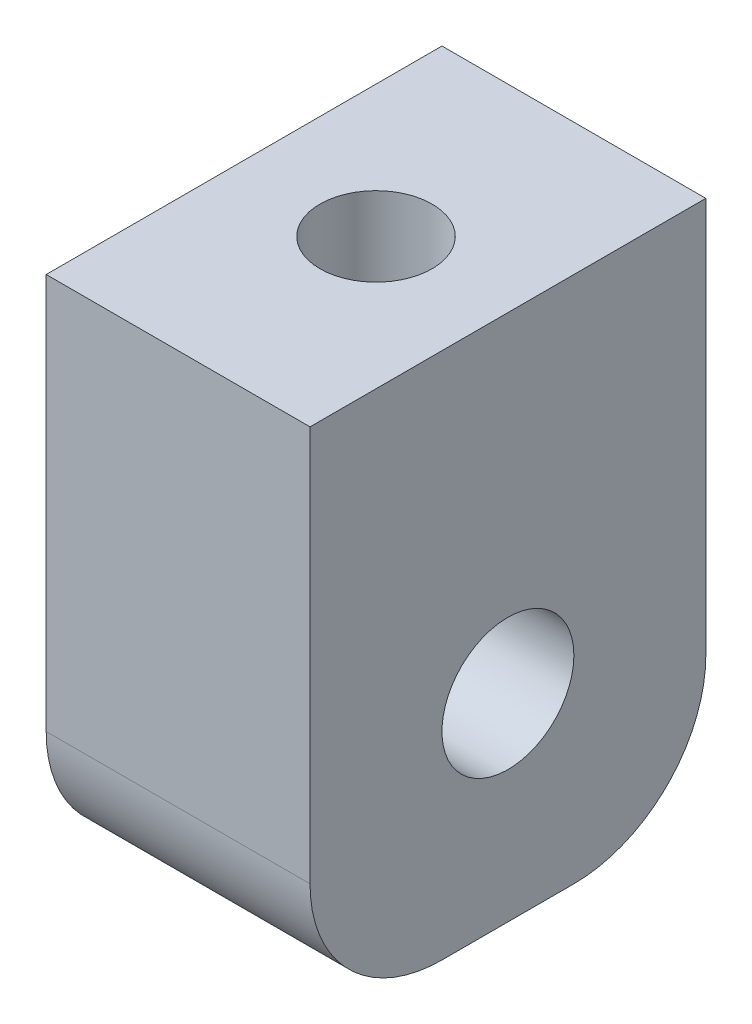
SolidWorks part; units mm, degrees
ref_plane "Front Plane" through (0, 0, 0) normal (0, 0, 1) x (1, 0, 0)
ref_plane "Top Plane" through (0, 0, 0) normal (0, 1, 0) x (1, 0, 0)
ref_plane "Right Plane" through (0, 0, 0) normal (1, 0, 0) x (0, 0, -1)
sketch "Sketch1" plane through (0, 0, 0) normal (0, 1, 0) x (1, 0, 0)
  line L1 (-10, 15) -> (10, 15)
  line L2 (-10, 15) -> (-10, -15)
  line L3 (-10, -15) -> (10, -15)
  line L4 (10, 15) -> (10, -15)
  line L5 (-10, 15) -> (10, -15) construction
  line L6 (-10, -15) -> (10, 15) construction
  point P0 (0, 0)
  dimension "D1" = 20
  dimension "D2" = 30
extrude "Boss-Extrude1" add sketch "Sketch1" against normal blind 40
sketch "Sketch2" plane through (0, 0, 0) normal (0, 1, 0) x (1, 0, 0)
  line L1 (-10, -15) -> (10, -15) construction
  line L2 (-10, -15) -> (-10, 15) construction
  line L3 (-10, 15) -> (10, 15) construction
  line L4 (10, -15) -> (10, 15) construction
  line L5 (-10, -15) -> (10, 15) construction
  line L6 (-10, 15) -> (10, -15) construction
  circle A0 centre (0, 0) radius 4.25
  dimension "D3" = 8.5
  dimension "D1" = 20
  dimension "D2" = 30
extrude "Cut-Extrude1" cut sketch "Sketch2" against normal blind 15
thread "Thread1" pitch 1 start angle 0, offset 0, length 15, pitch 1, diameter 8.5
ref_plane "Plane1" through (4.25, -15, 0) normal (0, 0, 1) x (1, 0, 0)
sketch "Thread Profile1" plane through (4.25, -15, 0) normal (0, 0, 1) x (1, 0, 0)
  line L0 (0, 0) -> (0, 1) construction
  line L1 (0, 0) -> (0.5413, 0.3125)
  line L2 (0.5413, 0.3125) -> (0.5413, 0.4375)
  line L3 (0.5413, 0.4375) -> (0, 0.75)
  line L4 (0.5413, 0.375) -> (0, 0.375) construction
  line L11 (0, 0) -> (0, 0.75)
  point P2 (0, 0)
  dimension "Pitch" = 1
  dimension "Profile_Angle" = 60
  dimension "Profile_Land" = 0.125
  dimension "Profile_Height" = 0.5413
sketch "Sketch11" plane through (0, 0, 0) normal (1, 0, 0) x (0, 0, -1)
  line L1 (-15, 0) -> (15, 0) construction
  line L2 (-15, 0) -> (-15, -40) construction
  line L3 (-15, -40) -> (15, -40) construction
  line L4 (15, 0) -> (15, -40) construction
  circle A0 centre (0, -25) radius 5
  point P10 (0, 0)
  dimension "D1" = 10
  dimension "D2" = 15
  dimension "D3" = 15
extrude "Cut-Extrude2" cut sketch "Sketch11" against normal through all both and the other way through all
fillet "Fillet1" radius 10 2 edges at (0, -40, -15) (0, -40, 15)
